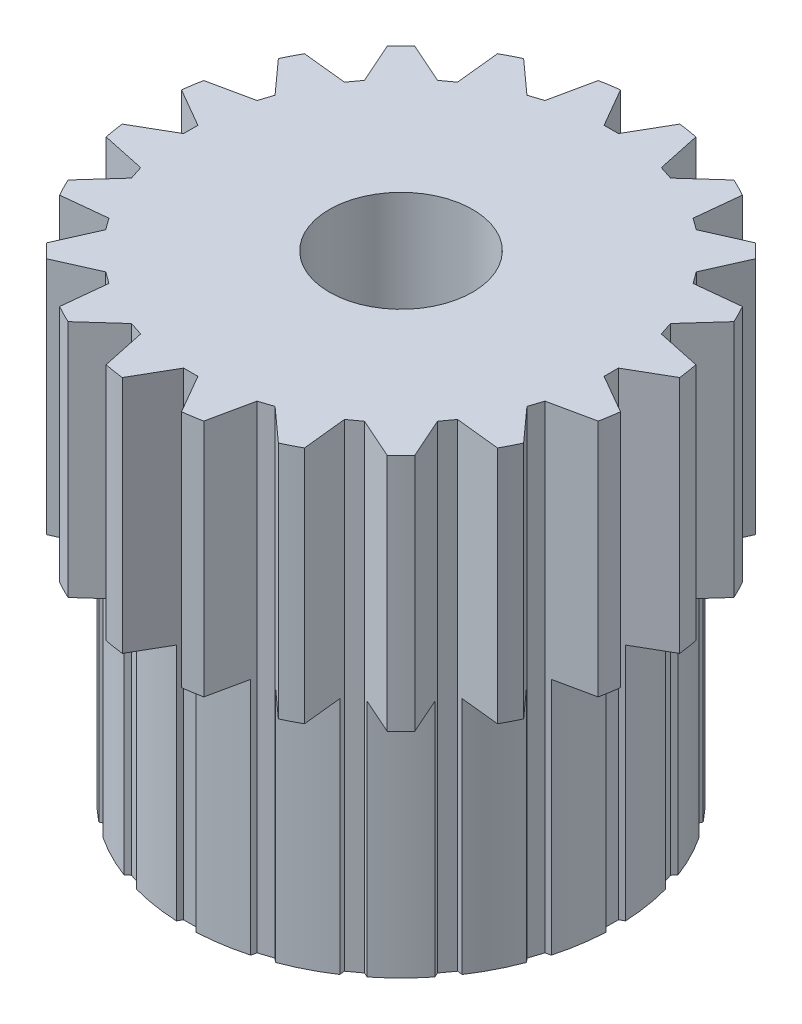
SolidWorks part; units mm, degrees
ref_plane "정면" through (0, 0, 0) normal (0, 0, 1) x (1, 0, 0)
ref_plane "윗면" through (0, 0, 0) normal (0, 1, 0) x (1, 0, 0)
ref_plane "우측면" through (0, 0, 0) normal (1, 0, 0) x (0, 0, -1)
sketch "스케치1" plane through (0, 0, 0) normal (0, 1, 0) x (1, 0, 0)
  circle A0 centre (0, 0) radius 4.5
  dimension "D1" = 9
extrude "보스-돌출1" add sketch "스케치1" along normal blind 10
sketch "스케치2" plane through (0, 10, 0) normal (0, 1, 0) x (1, 0, 0)
  circle A0 centre (0, 0) radius 5.25
  dimension "D1" = 10.5
extrude "보스-돌출2" add sketch "스케치2" against normal blind 5
sketch "스케치4" plane through (0, 10, 0) normal (0, 1, 0) x (1, 0, 0)
  line L0 (0, 0) -> (0, 5.25) construction
  line L1 (0, 4.4) -> (0.15, 4.4)
  line L2 (0.7274, 5.4) -> (0.15, 4.4)
  line L3 (0, 5.4) -> (0, 5.25) construction
  line L4 (0.7274, 5.4) -> (-0.7274, 5.4)
  line L5 (-0.7274, 5.4) -> (-0.15, 4.4)
  line L6 (-0.15, 4.4) -> (0, 4.4)
  circle A0 centre (0, 0) radius 5.25 construction
  dimension "D1" = 4.4
  dimension "D2" = 120
  dimension "D3" = 0.3
extrude "컷-돌출3" cut sketch "스케치4" against normal blind 10
pattern_circular "원형 패턴2" count 20 over 360 about axis through (0, 0, 0) along (0, 1, 0) of "컷-돌출3"
sketch "스케치5" plane through (0, 10, 0) normal (0, 1, 0) x (1, 0, 0)
  circle A0 centre (0, 0) radius 1.5
extrude "컷-돌출4" cut sketch "스케치5" against normal blind 10
